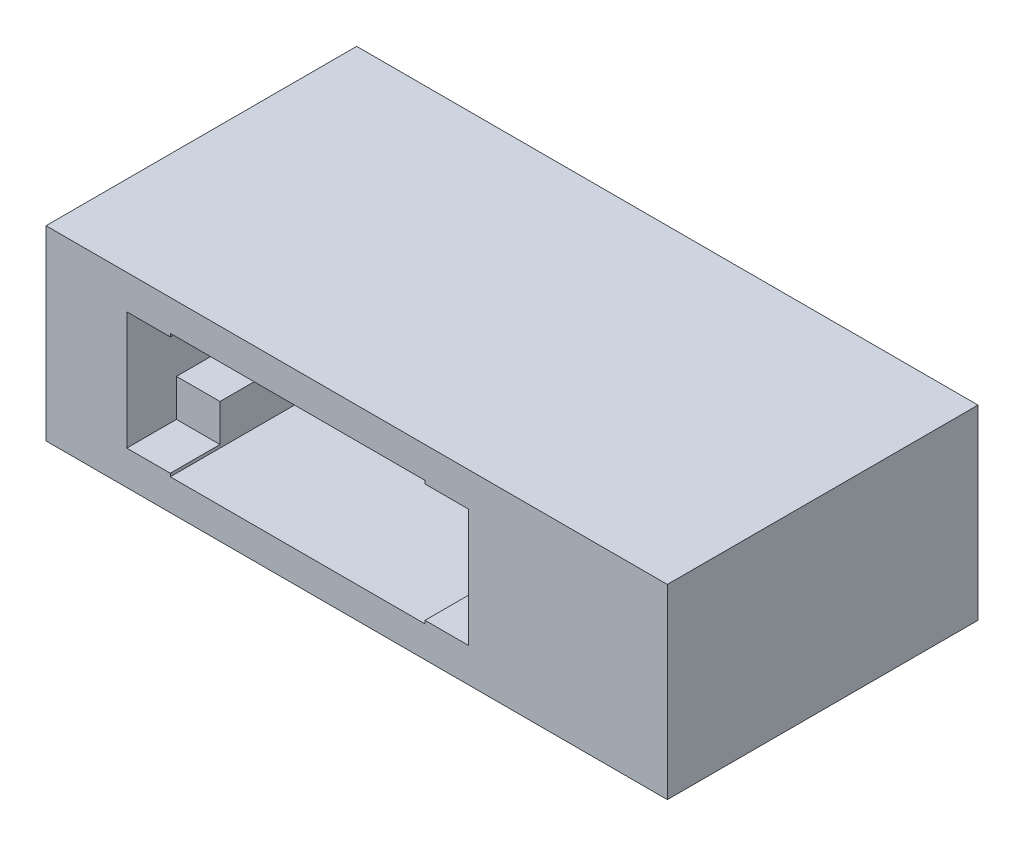
SolidWorks part; units mm, degrees
ref_plane "前基準面" through (0, 0, 0) normal (0, 0, 1) x (1, 0, 0)
ref_plane "上基準面" through (0, 0, 0) normal (0, 1, 0) x (1, 0, 0)
ref_plane "右基準面" through (0, 0, 0) normal (1, 0, 0) x (0, 0, -1)
sketch "草圖1" plane through (0, 0, 0) normal (0, 0, 1) x (1, 0, 0)
  line L1 (-36.9699, 18.8953) -> (63.0301, 18.8953)
  line L2 (-36.9699, 18.8953) -> (-36.9699, -11.1047)
  line L3 (-36.9699, -11.1047) -> (63.0301, -11.1047)
  line L4 (63.0301, 18.8953) -> (63.0301, -11.1047)
  dimension "D1" = 100
  dimension "D2" = 30
extrude "填料-伸長1" add sketch "草圖1" along normal blind 50 contours L2 L1 L4 L3
sketch "草圖2" plane through (0, 0, 50) normal (0, 0, 1) x (1, 0, 0)
  line L0 (-36.9699, -11.1047) -> (63.0301, -11.1047) construction
  line L1 (-16.9699, 13.8953) -> (24.0301, 13.8953)
  line L2 (-16.9699, 13.8953) -> (-16.9699, -6.1047)
  line L3 (-16.9699, -6.1047) -> (24.0301, -6.1047)
  line L4 (24.0301, 13.8953) -> (24.0301, -6.1047)
  line L5 (-36.9699, 18.8953) -> (-36.9699, -11.1047) construction
  dimension "D1" = 41
  dimension "D2" = 20
  dimension "D3" = 5
  dimension "D4" = 20
extrude "除料-伸長1" cut sketch "草圖2" against normal blind 37 contours L2 L1 L4 L3
sketch "草圖3" plane through (0, 0, 50) normal (0, 0, 1) x (1, 0, 0)
  line L0 (24.0301, 13.8953) -> (24.0301, -6.1047) construction
  line L1 (24.0301, 13.3953) -> (31.0301, 13.3953)
  line L2 (24.0301, 13.3953) -> (24.0301, -5.6047)
  line L3 (24.0301, -5.6047) -> (31.0301, -5.6047)
  line L4 (31.0301, 13.3953) -> (31.0301, -5.6047)
  line L5 (-16.9699, 13.8953) -> (-16.9699, -6.1047) construction
  line L6 (-16.9699, 13.3953) -> (-23.9699, 13.3953)
  line L7 (-16.9699, 13.3953) -> (-16.9699, -5.6047)
  line L8 (-16.9699, -5.6047) -> (-23.9699, -5.6047)
  line L9 (-23.9699, 13.3953) -> (-23.9699, -5.6047)
  line L10 (-36.9699, 18.8953) -> (63.0301, 18.8953) construction
  dimension "D1" = 7
  dimension "D2" = 7
  dimension "D3" = 19
  dimension "D4" = 19
  dimension "D5" = 5.5
  dimension "D6" = 5.5
extrude "除料-伸長2" cut sketch "草圖3" against normal blind 8
sketch "草圖4" plane through (0, 0, 42) normal (0, 0, 1) x (1, 0, 0)
  line L0 (-16.9699, -5.6047) -> (-16.9699, 13.3953) construction
  line L1 (-16.9699, 7.3953) -> (-23.9699, 7.3953)
  line L2 (-16.9699, 7.3953) -> (-16.9699, 0.3953)
  line L3 (-16.9699, 0.3953) -> (-23.9699, 0.3953)
  line L4 (-23.9699, 7.3953) -> (-23.9699, 0.3953)
  line L5 (-23.9699, 13.3953) -> (-23.9699, -5.6047) construction
  line L6 (-23.9699, -5.6047) -> (-16.9699, -5.6047) construction
  dimension "D1" = 7
  dimension "D2" = 6
extrude "除料-伸長3" cut sketch "草圖4" against normal blind 29
sketch "草圖5" plane through (0, 0, 13) normal (0, 0, 1) x (1, 0, 0)
  line L1 (-23.9699, 7.3953) -> (24.0301, 7.3953)
  line L2 (-23.9699, 7.3953) -> (-23.9699, 0.3953)
  line L3 (-23.9699, 0.3953) -> (24.0301, 0.3953)
  line L4 (24.0301, 7.3953) -> (24.0301, 0.3953)
  dimension "D1" = 7
  dimension "D2" = 48
extrude "除料-伸長4" cut sketch "草圖5" against normal blind 5
sketch "草圖6" plane through (0, 0, 8) normal (0, 0, 1) x (1, 0, 0)
  line L0 (24.0301, 0.3953) -> (24.0301, 7.3953) construction
  line L1 (24.0301, 7.3953) -> (19.0301, 7.3953)
  line L2 (24.0301, 7.3953) -> (24.0301, 0.3953)
  line L3 (24.0301, 0.3953) -> (19.0301, 0.3953)
  line L4 (19.0301, 7.3953) -> (19.0301, 0.3953)
  line L5 (24.0301, 7.3953) -> (-23.9699, 7.3953) construction
  line L6 (-23.9699, 0.3953) -> (24.0301, 0.3953) construction
  dimension "D1" = 5
extrude "除料-伸長5" cut sketch "草圖6" against normal up to next
sketch "草圖7" plane through (0, 0, 0) normal (0, 0, -1) x (-1, 0, 0)
  line L0 (36.9699, 18.8953) -> (36.9699, -11.1047) construction
  line L1 (36.9699, 18.8953) -> (-63.0301, 18.8953) construction
  circle A0 centre (7.9699, 3.8953) radius 2.5
  dimension "D2" = 5
  dimension "D3" = 15
  dimension "D1" = 29
extrude "除料-伸長6" cut sketch "草圖7" against normal up to next
